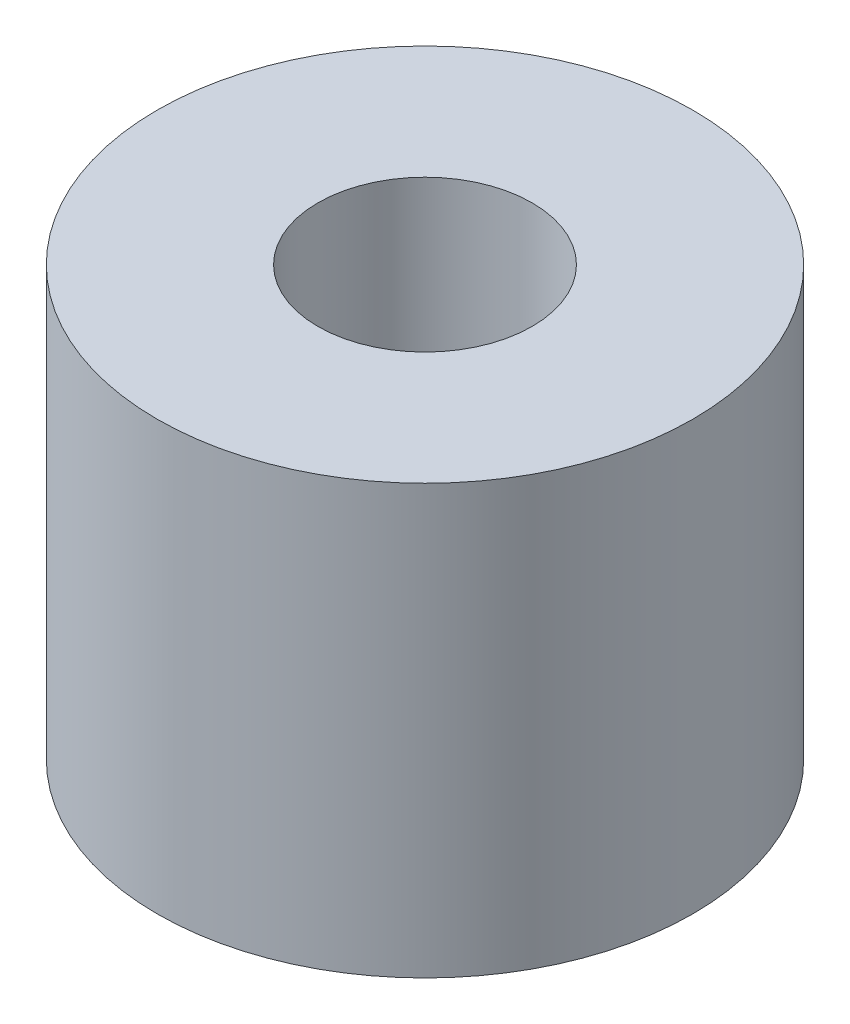
SolidWorks part; units mm, degrees
ref_plane "前视基准面" through (0, 0, 0) normal (0, 0, 1) x (1, 0, 0)
ref_plane "上视基准面" through (0, 0, 0) normal (0, 1, 0) x (1, 0, 0)
ref_plane "右视基准面" through (0, 0, 0) normal (1, 0, 0) x (0, 0, -1)
other "Configuration Table"
sketch "草图1" plane through (0, 0, 0) normal (0, 1, 0) x (1, 0, 0)
  circle A0 centre (0, 0) radius 2
  circle A1 centre (0, 0) radius 5
extrude "凸台-拉伸1" add sketch "草图1" along normal blind 8
